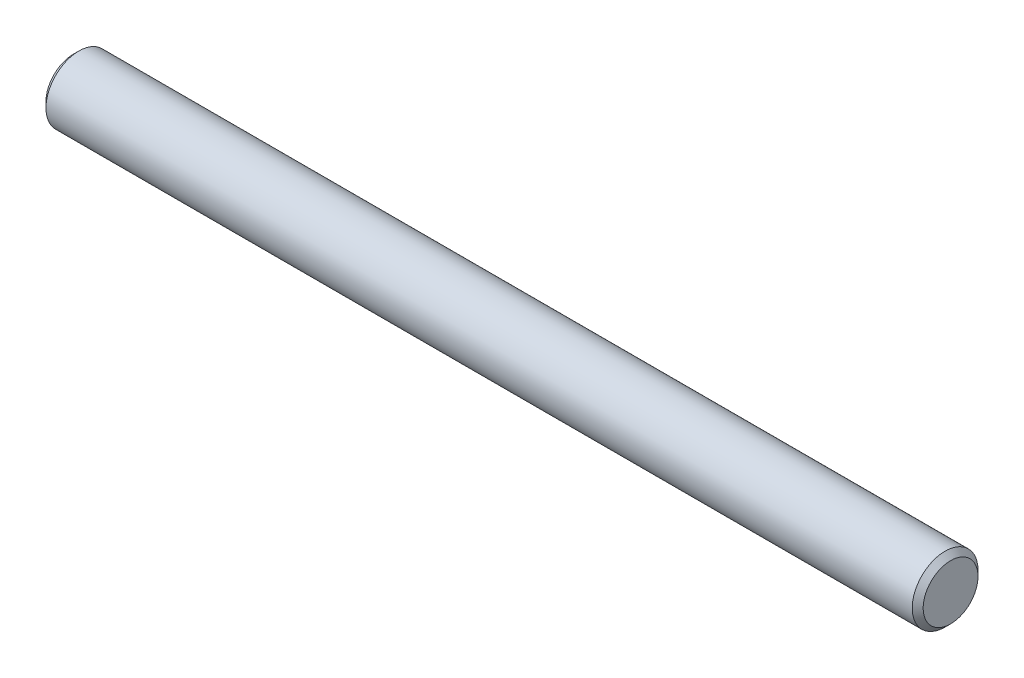
SolidWorks part; units mm, degrees
ref_plane "Front Plane" through (0, 0, 0) normal (0, 0, 1) x (1, 0, 0)
ref_plane "Top Plane" through (0, 0, 0) normal (0, 1, 0) x (1, 0, 0)
ref_plane "Right Plane" through (0, 0, 0) normal (1, 0, 0) x (0, 0, -1)
sketch "Sketch1" plane through (0, 0, 0) normal (1, 0, 0) x (0, 0, -1)
  circle A0 centre (0, 0) radius 1.5
  dimension "D1" = 3
extrude "Boss-Extrude1" add sketch "Sketch1" along normal mid plane 40
chamfer "Chamfer1" distance 0.25 angle 45 2 edges at (-20, 0, -1.5) (20, 0, -1.5)
